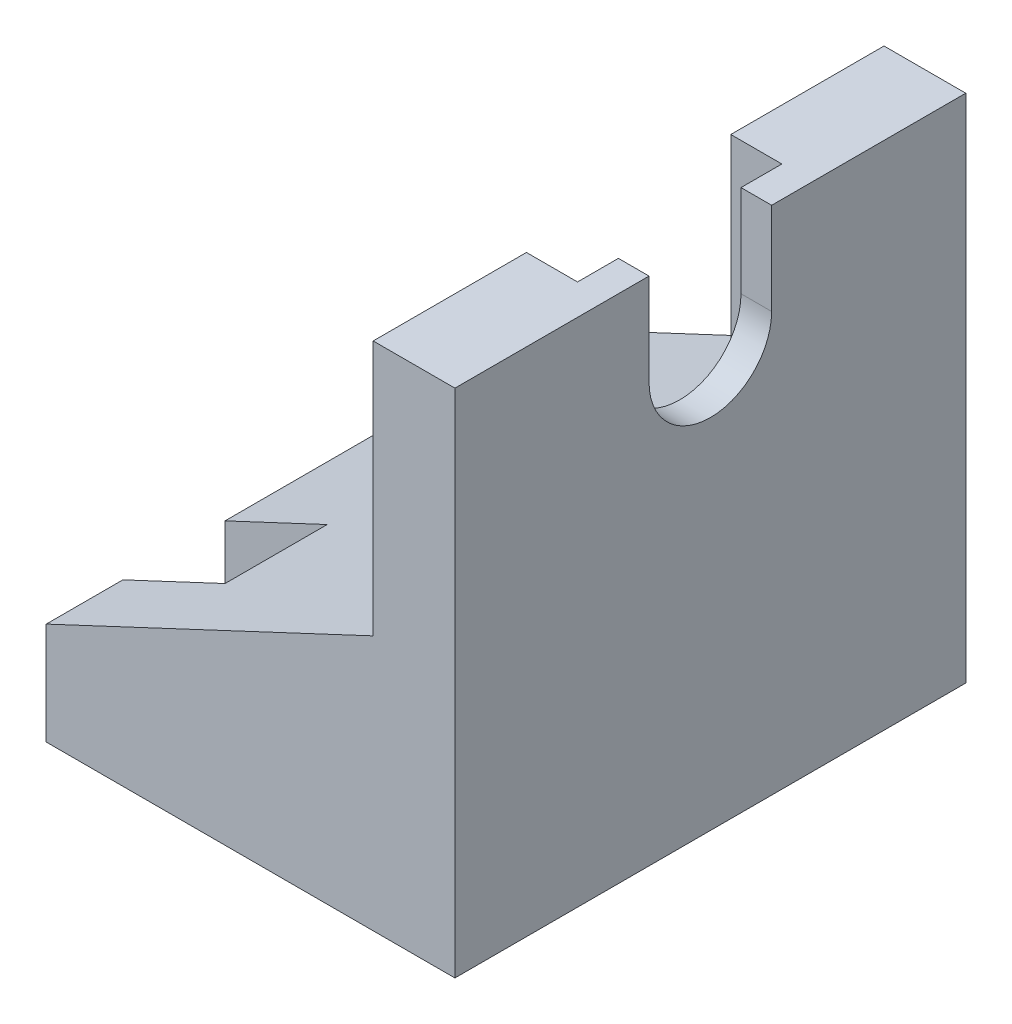
SolidWorks part; units mm, degrees
ref_plane "Спереди" through (0, 0, 0) normal (0, 0, 1) x (1, 0, 0)
ref_plane "Сверху" through (0, 0, 0) normal (0, 1, 0) x (1, 0, 0)
ref_plane "Справа" through (0, 0, 0) normal (1, 0, 0) x (0, 0, -1)
sketch "Эскиз1" plane through (0, 0, 0) normal (0, 0, 1) x (1, 0, 0)
  line L0 (12, 25) -> (12, 0)
  line L1 (-20, -25) -> (20, -25)
  line L2 (-20, -25) -> (-20, 25)
  line L3 (-20, 25) -> (20, 25)
  line L4 (20, -25) -> (20, 25)
  line L5 (-20, -25) -> (20, 25) construction
  line L6 (-20, 25) -> (20, -25) construction
  line L7 (12, 0) -> (-20, -15)
  point P0 (0, 0)
  dimension "D1" = 10
  dimension "D2" = 50
  dimension "D3" = 40
  dimension "D4" = 8
  dimension "D5" = 25
extrude "Бобышка-Вытянуть1" add sketch "Эскиз1" along normal blind 50 contours L0 L7 L2 L1 L4 L3
sketch "Эскиз2" plane through (0, -25, 0) normal (0, -1, 0) x (1, 0, 0)
  line L0 (-20, 25) -> (20, 25) construction
  line L1 (-20, 50) -> (-20, 0) construction
  line L2 (20, 50) -> (20, 0) construction
  line L3 (-20, 25) -> (-20, 50) construction
  line L4 (-20, 25) -> (-20, 0) construction
  line L5 (-20, 37.5) -> (20, 37.5) construction
  line L6 (-20, 12.5) -> (20, 12.5) construction
  line L8 (-10, 7.5) -> (-20, 7.5)
  line L9 (-10, 7.5) -> (-10, 17.5)
  line L10 (-10, 17.5) -> (-20, 17.5)
  line L11 (-20, 7.5) -> (-20, 17.5)
  line L12 (-10, 7.5) -> (-20, 17.5) construction
  line L13 (-10, 17.5) -> (-20, 7.5) construction
  line L14 (-10, 32.5) -> (-20, 32.5)
  line L15 (-10, 32.5) -> (-10, 42.5)
  line L16 (-10, 42.5) -> (-20, 42.5)
  line L17 (-20, 32.5) -> (-20, 42.5)
  line L18 (-10, 32.5) -> (-20, 42.5) construction
  line L19 (-10, 42.5) -> (-20, 32.5) construction
  point P14 (-15, 12.5)
  point P19 (-15, 37.5)
  dimension "D1" = 10
  dimension "D2" = 10
extrude "Вырез-Вытянуть1" cut sketch "Эскиз2" against normal through all
sketch "Эскиз3" plane through (20, 0, 0) normal (1, 0, 0) x (0, 0, -1)
  line L0 (-25, 25) -> (-25, -25) construction
  line L1 (-50, 25) -> (0, 25) construction
  line L2 (-50, -25) -> (0, -25) construction
  line L3 (-31, 16) -> (-31, 25)
  line L4 (-31, 25) -> (-19, 25)
  line L5 (-19, 25) -> (-19, 16)
  circle A0 centre (-25, 16) radius 6
  line M2 (0, 25) -> (-50, 25)
  dimension "D1" = 12
  dimension "D2" = 9
extrude "Вырез-Вытянуть2" cut sketch "Эскиз3" against normal blind 50 contours L0 A0 L5 M2 | A0 L0 | L0 A0 | L0 L4 L3 A0
ref_plane "Плоскость1" through (0, 0, 25) normal (0, 0, 1) x (1, 0, 0)
sketch "Эскиз4" plane through (0, 0, 25) normal (0, 0, 1) x (1, 0, 0)
  line L0 (12, 25) -> (12, 5)
  line L1 (12, 25) -> (12, 0) construction
  line L2 (12, 5) -> (17, 8)
  line L3 (17, 8) -> (17, 25)
  line L4 (12, 25) -> (20, 25) construction
  line L5 (17, 25) -> (12, 25)
  dimension "D1" = 20
  dimension "D2" = 5
  dimension "D3" = 17
extrude "Вырез-Вытянуть3" cut sketch "Эскиз4" against normal blind 10 and the other way blind 10
